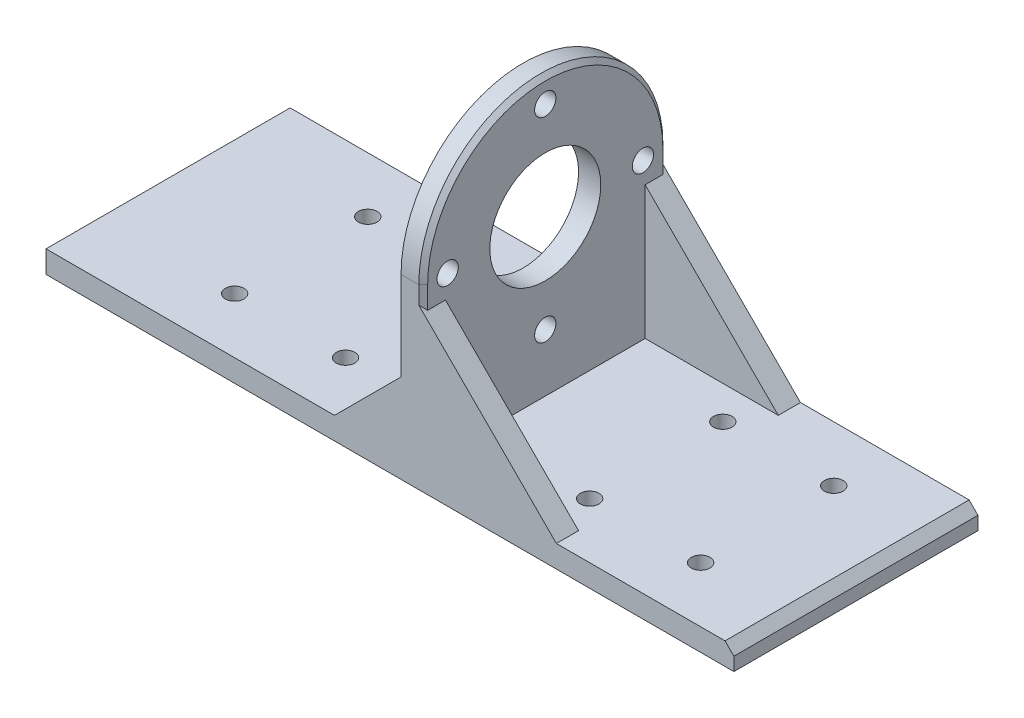
SolidWorks part; units mm, degrees
ref_plane "Front" through (0, 0, 0) normal (0, 0, 1) x (1, 0, 0)
ref_plane "Top" through (0, 0, 0) normal (0, 1, 0) x (1, 0, 0)
ref_plane "Right" through (0, 0, 0) normal (1, 0, 0) x (0, 0, -1)
sketch "草图1" plane through (0, 0, 0) normal (1, 0, 0) x (0, 0, -1)
  line L0 (-27.5, 0) -> (-27.5, -40)
  line L1 (-27.5, -40) -> (27.5, -40)
  line L2 (27.5, -40) -> (27.5, 0)
  arc A0 (27.5, 0) -> (-27.5, 0) centre (0, 0) ccw
  circle A1 centre (0, 0) radius 22 construction
  circle A2 centre (0, 0) radius 12.5
  circle A3 centre (0, 22) radius 2.4
  circle A4 centre (22, 0) radius 2.4
  circle A5 centre (0, -22) radius 2.4
  circle A6 centre (-22, 0) radius 2.4
extrude "凸台-拉伸1" add sketch "草图1" along normal blind 5
sketch "草图2" plane through (0, 0, 0) normal (-1, 0, 0) x (0, 0, 1)
  line L0 (27.5, 0) -> (27.5, -40) construction
  line L1 (-27.5, -40) -> (27.5, -40)
  line L2 (-27.5, -40) -> (-27.5, -35)
  line L3 (-27.5, -35) -> (27.5, -35)
  line L4 (27.5, -40) -> (27.5, -35)
  line L5 (0, -35) -> (0, -40) construction
  line L6 (-27.5, -37.5) -> (27.5, -37.5) construction
  point P112 (0, -37.5)
extrude "凸台-拉伸2" add sketch "草图2" along normal blind 80 contours L3 L4 L1 L2
sketch3d "3D草图1" plane through (0, 0, 0) normal (0, 0, 1) x (1, 0, 0)
  dimension "D1" = 25
sketch "草图3" plane through (0, 0, 25) normal (0, 0, 1) x (1, 0, 0)
  line L0 (0, -35) -> (0, -20) construction
  line L1 (0, 0) -> (0, -35) construction
  line L2 (0, -35) -> (-15, -35) construction
  line L3 (-80, -35) -> (0, -35) construction
  line L4 (-15, -35) -> (0, -20)
  dimension "D1" = 15
  dimension "D2" = 15
rib "筋1" sketch "草图3" sketch "草图3" thickness 5 extrusion direction parallel to sketch draft on no parameters "D1"=5
mirror "镜向1" about plane through (0, 0, 0) normal (0, 0, 1) of "筋1"
chamfer "倒角2" distance 2 angle 45 1 edges at (0, -35, 0)
sketch "草图4" plane through (5, 0, 0) normal (1, 0, 0) x (0, 0, -1)
  line L0 (27.5, -40) -> (27.5, 0) construction
  line L1 (-27.5, -40) -> (27.5, -40)
  line L2 (-27.5, -40) -> (-27.5, -35)
  line L3 (-27.5, -35) -> (27.5, -35)
  line L4 (27.5, -40) -> (27.5, -35)
  line L5 (0, -35) -> (0, -40) construction
  line L6 (-27.5, -37.5) -> (27.5, -37.5) construction
  point P160 (0, -37.5)
extrude "凸台-拉伸3" add sketch "草图4" along normal blind 70
sketch "草图5" plane through (0, 0, 25) normal (0, 0, 1) x (1, 0, 0)
  line L0 (5, -35) -> (5, -5) construction
  line L1 (5, 0) -> (5, -35) construction
  line L2 (5, -35) -> (35, -35) construction
  line L3 (75, -35) -> (5, -35) construction
  line L4 (35, -35) -> (5, -5)
rib "筋6" sketch "草图5" sketch "草图5" thickness 5 extrusion direction parallel to sketch draft on no parameters "D1"=5
mirror "镜向2" about plane through (0, 0, 0) normal (0, 0, 1) of "筋6"
sketch "草图6" plane through (0, -35, 0) normal (0, 1, 0) x (1, 0, 0)
  line L0 (5, 0) -> (5, 15) construction
  line L1 (5, 22.5) -> (5, -22.5) construction
  line L2 (5, 15) -> (75, 15) construction
  line L3 (75, 27.5) -> (75, -27.5) construction
  line L4 (5, 15) -> (-80, 15) construction
  line L5 (-80, 27.5) -> (-80, -27.5) construction
  line L6 (5, 15) -> (30, 15) construction
  line L7 (30, 15) -> (55, 15) construction
  line L8 (5, 15) -> (-25, 15) construction
  line L9 (-25, 15) -> (-50, 15) construction
  line L10 (0, 0) -> (20, 0) construction
  line L11 (-80, 27.5) -> (-15, 27.5) construction
  circle A0 centre (30, 15) radius 2.1
  circle A1 centre (55, 15) radius 2.1
  circle A2 centre (-50, 15) radius 2.1
  circle A3 centre (-25, 15) radius 2.1
  circle A4 centre (55, -15) radius 2.1
  circle A5 centre (30, -15) radius 2.1
  circle A6 centre (-25, -15) radius 2.1
  circle A7 centre (-50, -15) radius 2.1
  dimension "D1" = 30
  dimension "D2" = 25
  dimension "D3" = 20
  dimension "D4" = 25
  dimension "D5" = 12.5
extrude "切除-拉伸1" cut sketch "草图6" against normal up to next
chamfer "倒角3" distance 1 angle 45 3 edges at (5, -2.5, -27.5) (5, -2.5, 27.5) (5, 27.5, 0)
chamfer "倒角4" distance 2 angle 45 1 edges at (75, -35, 0)
